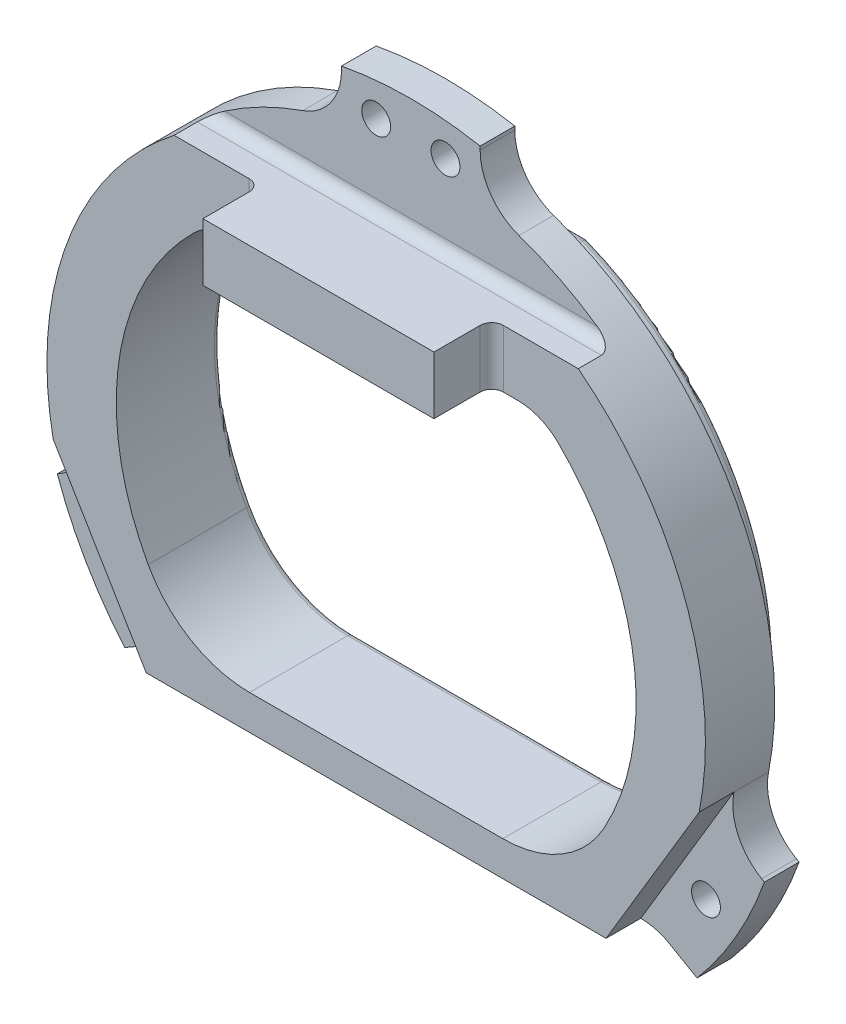
SolidWorks part; units mm, degrees
ref_plane "Front Plane" through (0, 0, 0) normal (0, 0, 1) x (1, 0, 0)
ref_plane "Top Plane" through (0, 0, 0) normal (0, 1, 0) x (1, 0, 0)
ref_plane "Right Plane" through (0, 0, 0) normal (1, 0, 0) x (0, 0, -1)
sketch "Sketch1" plane through (0, 0, 25) normal (0, 0, 1) x (1, 0, 0)
  line L24 (0, 32.5) -> (0, 19.8613)
  line L25 (0, 19.8613) -> (6, 19.8613)
  line L26 (6, 19.8613) -> (6, 24)
  line L27 (17.7482, -19) -> (19.9029, -19)
  line L81 (22.4029, -19.6699) -> (24.7722, -21.0378)
  line L82 (30.6054, -10.9345) -> (30.3696, -10.7984)
  line L83 (6, 31.6425) -> (6, 31.9414)
  line L85 (0, 19.8613) -> (6, 19.8613)
  line L86 (6, 19.8613) -> (6, 24)
  line L87 (17.7482, -19) -> (19.9029, -19)
  line L88 (22.4029, -19.6699) -> (24.7722, -21.0378)
  line L89 (30.6054, -10.9345) -> (30.3696, -10.7984)
  line L90 (6, 31.6425) -> (6, 31.9414)
  line L91 (-6, 19.8613) -> (0, 19.8613)
  line L92 (0, 19.8613) -> (0, 32.5)
  line L93 (-6, 31.9414) -> (-6, 31.6425)
  line L94 (-30.3696, -10.7984) -> (-30.6054, -10.9345)
  line L97 (-24.7722, -21.0378) -> (-22.4029, -19.6699)
  line L98 (-19.9029, -19) -> (-17.7482, -19)
  line L99 (-6, 24) -> (-6, 19.8613)
  line L100 (-6, 19.8613) -> (0, 19.8613)
  line L103 (-6, 31.9414) -> (-6, 31.6425)
  line L104 (-30.3696, -10.7984) -> (-30.6054, -10.9345)
  line L105 (-24.7722, -21.0378) -> (-22.4029, -19.6699)
  line L106 (-19.9029, -19) -> (-17.7482, -19)
  line L107 (-6, 24) -> (-6, 19.8613)
  arc A101 (7.28, 24.96) -> (6, 24) centre (7, 24) ccw
  arc A102 (17.7482, -19) -> (7.28, 24.96) centre (0, 0) ccw
  arc A103 (22.4029, -19.6699) -> (19.9029, -19) centre (19.9029, -24) ccw
  arc A104 (24.7722, -21.0378) -> (30.6054, -10.9345) centre (0, 0) ccw
  arc A105 (27.9637, -5.5028) -> (30.3696, -10.7984) centre (32.8696, -6.4682) ccw
  arc A106 (27.9637, -5.5028) -> (9.3582, 26.9198) centre (0, 0) ccw
  arc A107 (6, 31.6425) -> (9.3582, 26.9198) centre (11, 31.6425) ccw
  arc A108 (6, 31.9414) -> (0, 32.5) centre (0, 0) ccw
  arc A109 (7.28, 24.96) -> (6, 24) centre (7, 24) ccw
  arc A138 (17.7482, -19) -> (7.28, 24.96) centre (0, 0) ccw
  arc A139 (22.4029, -19.6699) -> (19.9029, -19) centre (19.9029, -24) ccw
  arc A140 (24.7722, -21.0378) -> (30.6054, -10.9345) centre (0, 0) ccw
  arc A141 (27.9637, -5.5028) -> (30.3696, -10.7984) centre (32.8696, -6.4682) ccw
  arc A142 (27.9637, -5.5028) -> (9.3582, 26.9198) centre (0, 0) ccw
  arc A143 (6, 31.6425) -> (9.3582, 26.9198) centre (11, 31.6425) ccw
  arc A144 (6, 31.9414) -> (0, 32.5) centre (0, 0) ccw
  arc A145 (0, 32.5) -> (-6, 31.9414) centre (0, 0) ccw
  arc A146 (-9.3582, 26.9198) -> (-6, 31.6425) centre (-11, 31.6425) ccw
  arc A147 (-9.3582, 26.9198) -> (-27.9637, -5.5028) centre (0, 0) ccw
  arc A148 (-30.3696, -10.7984) -> (-27.9637, -5.5028) centre (-32.8696, -6.4682) ccw
  arc A149 (-30.6054, -10.9345) -> (-24.7722, -21.0378) centre (0, 0) ccw
  arc A150 (-19.9029, -19) -> (-22.4029, -19.6699) centre (-19.9029, -24) ccw
  arc A151 (-7.28, 24.96) -> (-17.7482, -19) centre (0, 0) ccw
  arc A152 (-6, 24) -> (-7.28, 24.96) centre (-7, 24) ccw
  arc A153 (0, 32.5) -> (-6, 31.9414) centre (0, 0) ccw
  arc A154 (-9.3582, 26.9198) -> (-6, 31.6425) centre (-11, 31.6425) ccw
  arc A155 (-9.3582, 26.9198) -> (-27.9637, -5.5028) centre (0, 0) ccw
  arc A156 (-30.3696, -10.7984) -> (-27.9637, -5.5028) centre (-32.8696, -6.4682) ccw
  arc A157 (-30.6054, -10.9345) -> (-24.7722, -21.0378) centre (0, 0) ccw
  arc A158 (-19.9029, -19) -> (-22.4029, -19.6699) centre (-19.9029, -24) ccw
  arc A159 (-7.28, 24.96) -> (-17.7482, -19) centre (0, 0) ccw
  arc A160 (-6, 24) -> (-7.28, 24.96) centre (-7, 24) ccw
  dimension "D1" = 0
  dimension "D2" = 0
extrude "BASE EXTRUDE" add sketch "Sketch1" along normal blind 3
sketch "Sketch3" plane through (0, 0, 28) normal (0, 0, 1) x (1, 0, 0)
  line L0 (-17.7482, -19) -> (17.7482, -19)
  arc A0 (17.7482, -19) -> (-17.7482, -19) centre (0, 0) ccw
  dimension "D1" = 52
  dimension "D2" = 19
extrude "BASE CENTER FILL" add sketch "Sketch3" against normal blind 3
sketch "Sketch4" plane through (0, 0, 25) normal (0, 0, -1) x (-1, 0, 0)
  line L2 (-9.25, 23.7632) -> (-6.25, 23.7632)
  line L4 (-6.25, 23.7632) -> (-6.25, 19.5)
  line L5 (-6.25, 19.5) -> (6.25, 19.5)
  line L7 (6.25, 19.5) -> (6.25, 23.7632)
  line L8 (6.25, 23.7632) -> (9.25, 23.7632)
  arc A0 (-9.25, 23.7632) -> (9.25, 23.7632) centre (0, 0) ccw
  point P1 (0, 19.5)
  dimension "D1" = 51
  dimension "D2" = 12.5
  dimension "D3" = 19.5
  dimension "D4" = 3
extrude "HYDRA CRADDLE INSERT" add sketch "Sketch4" along normal blind 3
sketch "Sketch5" plane through (0, 0, 22) normal (0, 0, -1) x (-1, 0, 0)
  line L1 (-14.1421, 17.5) -> (14.1421, 17.5)
  line L2 (-17.0074, -19) -> (17.0074, -19) construction
  line L3 (-15.8193, -16) -> (15.8193, -16)
  line L4 (-6.25, 19.5) -> (6.25, 19.5) construction
  arc A7 (-8.1618, 20.9675) -> (-15.0065, -16.7647) centre (0, 0) ccw
  arc A8 (-14.1421, 17.5) -> (-15.8193, -16) centre (0, 0) ccw
  arc A10 (15.0065, -16.7647) -> (8.1618, 20.9675) centre (0, 0) ccw
  arc A11 (15.8193, -16) -> (14.1421, 17.5) centre (0, 0) ccw
  dimension "D4" = 2
  dimension "D3" = 3
  dimension "D1" = 3
  dimension "D2" = 3
extrude "WEIGHT RELIEF" cut sketch "Sketch5" against normal through all both and the other way through all
sketch "Sketch6" plane through (0, 0, 25) normal (0, 0, -1) x (-1, 0, 0)
  line L0 (28.1458, -16.25) -> (0, 0) construction
  line L1 (-28.1458, -16.25) -> (0, 0) construction
  line L2 (0, 0) -> (0, 32.5) construction
  line L3 (-6, 31.9414) -> (0, 31.9414) construction
  line L4 (6, 31.9414) -> (0, 31.9414) construction
  line L5 (0, 19.8613) -> (0, 32.5) construction
  circle A0 centre (-25.5477, -14.75) radius 1.25
  circle A1 centre (25.5477, -14.75) radius 1.25
  circle A2 centre (-3, 29.5) radius 1.25
  circle A3 centre (3, 29.5) radius 1.25
  arc A7 (6, 31.9414) -> (0, 32.5) centre (0, 0) ccw construction
  arc A8 (24.7722, -21.0378) -> (30.6054, -10.9345) centre (0, 0) ccw construction
  arc A9 (-30.6054, -10.9345) -> (-24.7722, -21.0378) centre (0, 0) ccw construction
  point P26 (-3, 31.9414)
  point P28 (3, 31.9414)
  dimension "D1" = 2.5
  dimension "D2" = 3
  dimension "D3" = 3
  dimension "D4" = 3
  dimension "D5" = 3
extrude "SCREWHOLES TO HYDRA CRADDLE" cut sketch "Sketch6" against normal blind 10
fillet "Fillet1" radius 10 2 edges at (-15.8193, -16, 25) (15.8193, -16, 25)
fillet "Fillet2" radius 5 2 edges at (-14.1421, 17.5, 25) (14.1421, 17.5, 25)
sketch "Sketch7" plane through (0, 0, 28) normal (0, 0, 1) x (1, 0, 0)
  line L0 (-9.3582, 26.9198) -> (9.3582, 26.9198)
  line L1 (19.9029, -19) -> (27.9637, -5.5028)
  line L2 (-19.9029, -19) -> (-27.9637, -5.5028)
  line L3 (10.9659, -16) -> (-10.9659, -16) construction
  line L4 (-12.2474, 17.5) -> (12.2474, 17.5) construction
  line L5 (10.9659, -16) -> (-10.9659, -16)
  line L6 (-12.2474, 17.5) -> (12.2474, 17.5)
  line L7 (-19.9029, -19) -> (19.9029, -19)
  line L8 (22.4029, -19.6699) -> (24.7722, -21.0378)
  line L9 (30.6054, -10.9345) -> (30.3696, -10.7984)
  line L10 (6, 31.6425) -> (6, 31.9414)
  line L11 (-6, 31.9414) -> (-6, 31.6425)
  line L12 (-30.3696, -10.7984) -> (-30.6054, -10.9345)
  line L13 (-24.7722, -21.0378) -> (-22.4029, -19.6699)
  line L14 (-19.9029, -19) -> (19.9029, -19)
  arc A0 (-19.7385, -10.8) -> (-10.9659, -16) centre (-10.9659, -6) ccw construction
  arc A1 (10.9659, -16) -> (19.7385, -10.8) centre (10.9659, -6) ccw construction
  arc A2 (19.7385, -10.8) -> (15.7467, 16.0714) centre (0, 0) ccw construction
  arc A3 (15.7467, 16.0714) -> (12.2474, 17.5) centre (12.2474, 12.5) ccw construction
  arc A4 (-15.7467, 16.0714) -> (-19.7385, -10.8) centre (0, 0) ccw construction
  arc A5 (-12.2474, 17.5) -> (-15.7467, 16.0714) centre (-12.2474, 12.5) ccw construction
  arc A6 (-19.7385, -10.8) -> (-10.9659, -16) centre (-10.9659, -6) ccw
  arc A7 (10.9659, -16) -> (19.7385, -10.8) centre (10.9659, -6) ccw
  arc A8 (19.7385, -10.8) -> (15.7467, 16.0714) centre (0, 0) ccw
  arc A9 (15.7467, 16.0714) -> (12.2474, 17.5) centre (12.2474, 12.5) ccw
  arc A10 (-15.7467, 16.0714) -> (-19.7385, -10.8) centre (0, 0) ccw
  arc A11 (22.4029, -19.6699) -> (19.9029, -19) centre (19.9029, -24) ccw
  arc A12 (24.7722, -21.0378) -> (30.6054, -10.9345) centre (0, 0) ccw
  arc A13 (27.9637, -5.5028) -> (30.3696, -10.7984) centre (32.8696, -6.4682) ccw
  arc A14 (27.9637, -5.5028) -> (9.3582, 26.9198) centre (0, 0) ccw
  arc A15 (6, 31.6425) -> (9.3582, 26.9198) centre (11, 31.6425) ccw
  arc A16 (6, 31.9414) -> (-6, 31.9414) centre (0, 0) ccw
  arc A17 (-9.3582, 26.9198) -> (-6, 31.6425) centre (-11, 31.6425) ccw
  arc A18 (-9.3582, 26.9198) -> (-27.9637, -5.5028) centre (0, 0) ccw
  arc A19 (-30.3696, -10.7984) -> (-27.9637, -5.5028) centre (-32.8696, -6.4682) ccw
  arc A20 (-30.6054, -10.9345) -> (-24.7722, -21.0378) centre (0, 0) ccw
  arc A21 (-19.9029, -19) -> (-22.4029, -19.6699) centre (-19.9029, -24) ccw
  arc A25 (27.9637, -5.5028) -> (9.3582, 26.9198) centre (0, 0) ccw
  arc A29 (-9.3582, 26.9198) -> (-27.9637, -5.5028) centre (0, 0) ccw
  arc A33 (-12.2474, 17.5) -> (-15.7467, 16.0714) centre (-12.2474, 12.5) ccw
  dimension "D1" = 0
extrude "SPACER BETWEEN HYDRA STACK AND E-MATCH CRADDLES" add sketch "Sketch7" along normal blind 3
sketch "Sketch8" plane through (0, 0, 31) normal (0, 0, 1) x (1, 0, 0)
  line L0 (-17.4929, 22.5) -> (17.4929, 22.5)
  line L1 (12.2474, 17.5) -> (-12.2474, 17.5) construction
  line L2 (9.3582, 26.9198) -> (-9.3582, 26.9198) construction
  line L3 (9.3582, 26.9198) -> (-9.3582, 26.9198)
  arc A0 (-9.3582, 26.9198) -> (-27.9637, -5.5028) centre (0, 0) ccw construction
  arc A1 (27.9637, -5.5028) -> (9.3582, 26.9198) centre (0, 0) ccw construction
  arc A2 (-9.3582, 26.9198) -> (-17.4929, 22.5) centre (0, 0) ccw
  arc A3 (17.4929, 22.5) -> (9.3582, 26.9198) centre (0, 0) ccw
  dimension "D1" = 5
extrude "EMATCH WIRE CLEARANCE CUT" cut sketch "Sketch8" against normal up to surface (3 mm away) and the other way through all up to face at (25.9448, -14.5714, 28)
sketch "Sketch9" plane through (0, 0, 31) normal (0, 0, 1) x (1, 0, 0)
  line L0 (-17.4929, 22.5) -> (17.4929, 22.5) construction
  line L1 (-10, 22.5) -> (10, 22.5)
  line L2 (-10, 22.5) -> (-10, 17.5)
  line L3 (-10, 17.5) -> (10, 17.5)
  line L4 (10, 22.5) -> (10, 17.5)
  line L5 (12.2474, 17.5) -> (-12.2474, 17.5) construction
  point P8 (0, 17.5)
  dimension "D1" = 20
extrude "ALIGNMENT PEG WITH BLAST SHIELD" add sketch "Sketch9" along normal blind 5
fillet "Fillet3" radius 1 3 edges at (10, 20, 31) (-10, 20, 31) (0, 22.5, 28)
fillet "Fillet4" radius 0.5 28 edges at (6.25, 21.6316, 25) (6.25, 21.6316, 22) (0, 19.5, 22) (-6.25, 21.6316, 22) (-7.75, 23.7632, 22) (-25.0905, 4.5515, 22) (0, -19, 22) (25.0905, 4.5515, 22) (7.75, 23.7632, 22) (16.0649, -14.6023, 22) (0, -16, 22) (-16.0649, -14.6023, 22) (-22.2558, 3.3062, 22) (-14.1373, 17.1291, 22) (0, 17.5, 22) (14.1373, 17.1291, 22) (22.2558, 3.3062, 22) (-6.25, 23.7632, 23.5) (-6.25, 21.6316, 25) (0, 19.5, 25) (6.25, 19.5, 23.5) (6.25, 23.7632, 23.5) (7.75, 23.7632, 25) (9.25, 23.7632, 23.5) (-9.25, 23.7632, 23.5) (-7.75, 23.7632, 25) (-25.0905, 4.5515, 25) (25.0905, 4.5515, 25)
